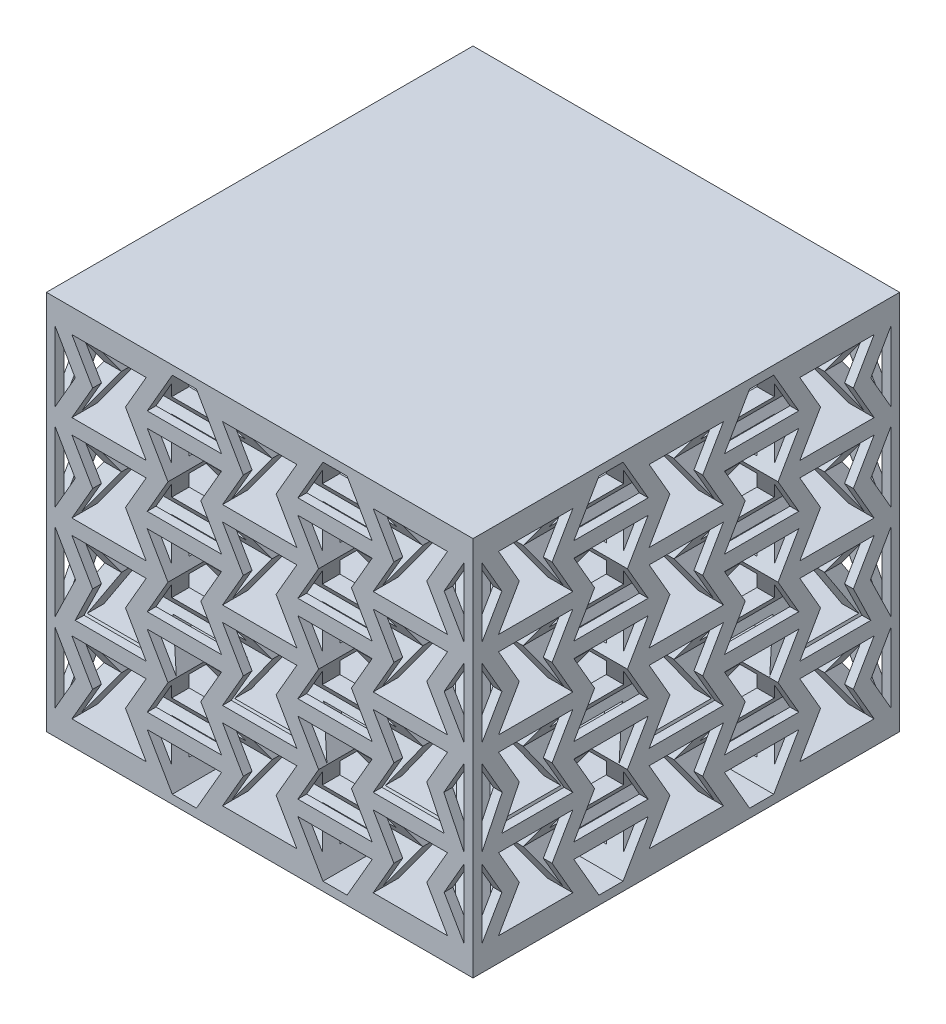
SolidWorks part; units mm, degrees
ref_plane "Front Plane" through (0, 0, 0) normal (0, 0, 1) x (1, 0, 0)
ref_plane "Top Plane" through (0, 0, 0) normal (0, 1, 0) x (1, 0, 0)
ref_plane "Right Plane" through (0, 0, 0) normal (1, 0, 0) x (0, 0, -1)
sketch "Sketch1" plane through (0, 0, 0) normal (0, 0, 1) x (1, 0, 0)
  line L0 (-9.5977, -9.2636) -> (10.4023, -9.2636) construction
  line L1 (10.4023, -9.2636) -> (5.4023, -0.6034) construction
  line L2 (5.4023, -0.6034) -> (10.4023, 8.0569) construction
  line L3 (10.4023, 8.0569) -> (-9.5977, 8.0569) construction
  line L4 (-9.5977, 8.0569) -> (-4.5977, -0.6034) construction
  line L5 (-4.5977, -0.6034) -> (-9.5977, -9.2636) construction
  line L6 (-9.5977, -26.5841) -> (10.4023, -26.5841) construction
  line L7 (10.4023, -26.5841) -> (5.4023, -17.9239) construction
  line L8 (5.4023, -17.9239) -> (10.4023, -9.2636) construction
  line L9 (-9.5977, -9.2636) -> (-4.5977, -17.9239) construction
  line L10 (-4.5977, -17.9239) -> (-9.5977, -26.5841) construction
  line L11 (-8.7413, -43.9047) -> (10.4023, -43.9047) construction
  line L12 (10.4023, -43.9047) -> (5.4023, -35.2444) construction
  line L13 (5.4023, -35.2444) -> (10.4023, -26.5841) construction
  line L14 (-9.5977, -26.5841) -> (-4.5628, -35.3049) construction
  line L15 (-4.5628, -35.3049) -> (-8.7413, -43.9047) construction
  line L16 (-9.5977, -61.2252) -> (10.4023, -61.2252) construction
  line L17 (10.4023, -61.2252) -> (5.4023, -52.5649) construction
  line L18 (5.4023, -52.5649) -> (10.4023, -43.9047) construction
  line L19 (-9.5977, -43.9047) -> (-4.5977, -52.5649) construction
  line L20 (-4.5977, -52.5649) -> (-9.5977, -61.2252) construction
  line L21 (5.4023, -0.6034) -> (25.4023, -0.6034) construction
  line L22 (5.4023, -17.9239) -> (25.4023, -17.9239) construction
  line L23 (20.4023, -9.2636) -> (40.4023, -9.2636) construction
  line L24 (40.4023, -9.2636) -> (35.4023, -0.6034) construction
  line L25 (5.4023, -35.2444) -> (25.4023, -35.2444) construction
  line L26 (5.4023, -52.5649) -> (25.4023, -52.5649) construction
  line L27 (35.4023, -0.6034) -> (40.4023, 8.0569) construction
  line L28 (40.4023, 8.0569) -> (20.4023, 8.0569) construction
  line L29 (20.4023, 8.0569) -> (25.4023, -0.6034) construction
  line L30 (25.4023, -0.6034) -> (20.4023, -9.2636) construction
  line L31 (20.4023, -26.5841) -> (40.4023, -26.5841) construction
  line L32 (40.4023, -26.5841) -> (35.4023, -17.9239) construction
  line L33 (35.4023, -17.9239) -> (40.4023, -9.2636) construction
  line L34 (20.4023, -9.2636) -> (25.4023, -17.9239) construction
  line L35 (25.4023, -17.9239) -> (20.4023, -26.5841) construction
  line L36 (20.4023, -43.9047) -> (40.4023, -43.9047) construction
  line L37 (40.4023, -43.9047) -> (35.4023, -35.2444) construction
  line L38 (35.4023, -35.2444) -> (40.4023, -26.5841) construction
  line L39 (20.4023, -26.5841) -> (25.4023, -35.2444) construction
  line L40 (25.4023, -35.2444) -> (20.4023, -43.9047) construction
  line L41 (20.4023, -61.2252) -> (40.4023, -61.2252) construction
  line L42 (40.4023, -61.2252) -> (35.4023, -52.5649) construction
  line L43 (35.4023, -52.5649) -> (40.4023, -43.9047) construction
  line L44 (20.4023, -43.9047) -> (25.4023, -52.5649) construction
  line L45 (25.4023, -52.5649) -> (20.4023, -61.2252) construction
  line L46 (35.4023, -0.6034) -> (55.4023, -0.6034) construction
  line L47 (35.4023, -17.9239) -> (55.4023, -17.9239) construction
  line L48 (35.4023, -35.2444) -> (55.4023, -35.2444) construction
  line L49 (35.4023, -52.5649) -> (55.4023, -52.5649) construction
  line L50 (50.4023, -9.2636) -> (70.4023, -9.2636) construction
  line L51 (70.4023, -9.2636) -> (65.4023, -0.6034) construction
  line L52 (65.4023, -0.6034) -> (70.4023, 8.0569) construction
  line L53 (70.4023, 8.0569) -> (50.4023, 8.0569) construction
  line L54 (50.4023, 8.0569) -> (55.4023, -0.6034) construction
  line L55 (55.4023, -0.6034) -> (50.4023, -9.2636) construction
  line L56 (50.4023, -26.5841) -> (70.4023, -26.5841) construction
  line L57 (70.4023, -26.5841) -> (65.4023, -17.9239) construction
  line L58 (65.4023, -17.9239) -> (70.4023, -9.2636) construction
  line L59 (50.4023, -9.2636) -> (55.4023, -17.9239) construction
  line L60 (55.4023, -17.9239) -> (50.4023, -26.5841) construction
  line L61 (50.4023, -43.9047) -> (69.5458, -43.9047) construction
  line L62 (69.5458, -43.9047) -> (65.3673, -35.3049) construction
  line L63 (65.3673, -35.3049) -> (70.4023, -26.5841) construction
  line L64 (50.4023, -26.5841) -> (55.4023, -35.2444) construction
  line L65 (55.4023, -35.2444) -> (50.4023, -43.9047) construction
  line L66 (50.4023, -61.2252) -> (70.4023, -61.2252) construction
  line L67 (70.4023, -61.2252) -> (65.4023, -52.5649) construction
  line L68 (65.4023, -52.5649) -> (70.4023, -43.9047) construction
  line L69 (50.4023, -43.9047) -> (55.4023, -52.5649) construction
  line L70 (55.4023, -52.5649) -> (50.4023, -61.2252) construction
  line L71 (-6.9997, -10.7636) -> (7.8042, -10.7636)
  line L72 (12.1343, -9.2636) -> (8.0003, -2.1034)
  line L73 (8.0003, 0.8966) -> (13.0003, 9.5569)
  line L75 (-10.3298, 6.3248) -> (-6.3298, -0.6034)
  line L76 (-6.3298, -0.6034) -> (-10.3298, -7.5316)
  line L77 (-10.3298, -10.9957) -> (-6.3298, -17.9239)
  line L78 (-6.3298, -17.9239) -> (-10.3298, -24.8521)
  line L80 (12.1343, -26.5841) -> (8.0003, -19.4239)
  line L81 (8.0003, -16.4239) -> (12.1343, -9.2636)
  line L82 (-10.3298, -28.3162) -> (-6.2599, -35.3655)
  line L83 (-6.2599, -35.3655) -> (-10.3298, -43.7416)
  line L85 (12.1343, -43.9047) -> (8.0003, -36.7444)
  line L86 (8.0003, -33.7444) -> (12.1343, -26.5841)
  line L87 (-10.3298, -45.6367) -> (-6.3298, -52.5649)
  line L88 (-6.3298, -52.5649) -> (-10.3298, -59.4931)
  line L90 (13.0003, -62.7252) -> (8.0003, -54.0649)
  line L91 (8.0003, -51.0649) -> (12.1343, -43.9047)
  line L92 (19.1032, -10.0136) -> (23.6702, -17.9239) construction
  line L93 (38.0003, -2.1034) -> (52.8042, -2.1034)
  line L94 (23.0003, -10.7636) -> (37.8042, -10.7636)
  line L95 (42.1343, -9.2636) -> (38.0003, -2.1034)
  line L96 (38.0003, 0.8966) -> (43.0003, 9.5569)
  line L98 (17.8042, 9.5569) -> (22.8042, 0.8966)
  line L99 (22.8042, -2.1034) -> (18.6702, -9.2636)
  line L100 (38.0003, -33.7444) -> (52.8042, -33.7444)
  line L101 (38.0003, -51.0649) -> (52.8042, -51.0649)
  line L102 (18.6702, -9.2636) -> (22.8042, -16.4239)
  line L103 (22.8042, -19.4239) -> (18.6702, -26.5841)
  line L105 (42.1343, -26.5841) -> (38.0003, -19.4239)
  line L106 (38.0003, -16.4239) -> (42.1343, -9.2636)
  line L107 (18.6702, -26.5841) -> (22.8042, -33.7444)
  line L108 (22.8042, -36.7444) -> (18.6702, -43.9047)
  line L110 (42.1343, -43.9047) -> (38.0003, -36.7444)
  line L111 (38.0003, -33.7444) -> (42.1343, -26.5841)
  line L112 (18.6702, -43.9047) -> (22.8042, -51.0649)
  line L113 (22.8042, -54.0649) -> (17.8042, -62.7252)
  line L115 (43.0003, -62.7252) -> (38.0003, -54.0649)
  line L116 (38.0003, -51.0649) -> (42.1343, -43.9047)
  line L117 (49.1032, -10.0136) -> (53.6702, -17.9239) construction
  line L118 (49.1032, -27.3341) -> (53.6702, -35.2444) construction
  line L119 (38.0003, -36.7444) -> (52.8042, -36.7444)
  line L120 (38.0003, -54.0649) -> (52.8042, -54.0649)
  line L122 (71.1343, -7.5316) -> (67.1343, -0.6034)
  line L123 (67.1343, -0.6034) -> (71.1343, 6.3248)
  line L125 (47.8042, 9.5569) -> (52.8042, 0.8966)
  line L126 (52.8042, -2.1034) -> (48.6702, -9.2636)
  line L127 (48.6702, -9.2636) -> (52.8042, -16.4239)
  line L128 (52.8042, -19.4239) -> (48.6702, -26.5841)
  line L129 (19.1032, -27.3341) -> (23.6702, -35.2444) construction
  line L130 (71.1343, -24.8521) -> (67.1343, -17.9239)
  line L131 (67.1343, -17.9239) -> (71.1343, -10.9957)
  line L132 (48.6702, -26.5841) -> (52.8042, -33.7444)
  line L133 (52.8042, -36.7444) -> (48.6702, -43.9047)
  line L135 (71.1343, -43.7416) -> (67.0644, -35.3655)
  line L136 (67.0644, -35.3655) -> (71.1343, -28.3162)
  line L137 (48.6702, -43.9047) -> (52.8042, -51.0649)
  line L138 (52.8042, -54.0649) -> (47.8042, -62.7252)
  line L140 (71.1343, -59.4931) -> (67.1343, -52.5649)
  line L141 (67.1343, -52.5649) -> (71.1343, -45.6367)
  line L142 (-6.9997, -7.7636) -> (7.8042, -7.7636)
  line L143 (7.8042, -7.7636) -> (3.6702, -0.6034)
  line L144 (3.6702, -0.6034) -> (7.8042, 6.5569)
  line L145 (7.8042, 6.5569) -> (-6.9997, 6.5569)
  line L146 (-6.9997, 6.5569) -> (-2.8657, -0.6034)
  line L147 (-2.8657, -0.6034) -> (-6.9997, -7.7636)
  line L148 (-6.9997, -10.7636) -> (-2.8657, -17.9239)
  line L149 (-2.8657, -17.9239) -> (-6.9997, -25.0841)
  line L150 (-6.9997, -25.0841) -> (7.8042, -25.0841)
  line L151 (7.8042, -25.0841) -> (3.6702, -17.9239)
  line L152 (3.6702, -17.9239) -> (7.8042, -10.7636)
  line L153 (-6.9997, -28.0841) -> (-2.8657, -35.2444)
  line L154 (-2.8657, -35.2444) -> (-6.3448, -42.4047)
  line L155 (-6.3448, -42.4047) -> (7.8042, -42.4047)
  line L156 (7.8042, -42.4047) -> (3.6702, -35.2444)
  line L157 (3.6702, -35.2444) -> (7.8042, -28.0841)
  line L158 (-6.9997, -45.4047) -> (-2.8657, -52.5649)
  line L159 (-2.8657, -52.5649) -> (-6.9997, -59.7252)
  line L160 (-6.9997, -59.7252) -> (7.8042, -59.7252)
  line L161 (7.8042, -59.7252) -> (3.6702, -52.5649)
  line L162 (3.6702, -52.5649) -> (7.8042, -45.4047)
  line L163 (8.0003, 0.8966) -> (22.8042, 0.8966)
  line L164 (8.0003, -16.4239) -> (22.8042, -16.4239)
  line L165 (23.0003, -7.7636) -> (37.8042, -7.7636)
  line L166 (37.8042, -7.7636) -> (33.6702, -0.6034)
  line L167 (33.6702, -0.6034) -> (37.8042, 6.5569)
  line L168 (37.8042, 6.5569) -> (23.0003, 6.5569)
  line L169 (23.0003, 6.5569) -> (27.1343, -0.6034)
  line L170 (27.1343, -0.6034) -> (23.0003, -7.7636)
  line L171 (8.0003, -33.7444) -> (22.8042, -33.7444)
  line L172 (8.0003, -51.0649) -> (22.8042, -51.0649)
  line L173 (23.0003, -10.7636) -> (27.1343, -17.9239)
  line L174 (27.1343, -17.9239) -> (23.0003, -25.0841)
  line L175 (23.0003, -25.0841) -> (37.8042, -25.0841)
  line L176 (37.8042, -25.0841) -> (33.6702, -17.9239)
  line L177 (33.6702, -17.9239) -> (37.8042, -10.7636)
  line L178 (23.0003, -28.0841) -> (27.1343, -35.2444)
  line L179 (27.1343, -35.2444) -> (23.0003, -42.4047)
  line L180 (23.0003, -42.4047) -> (37.8042, -42.4047)
  line L181 (37.8042, -42.4047) -> (33.6702, -35.2444)
  line L182 (33.6702, -35.2444) -> (37.8042, -28.0841)
  line L183 (23.0003, -45.4047) -> (27.1343, -52.5649)
  line L184 (27.1343, -52.5649) -> (23.0003, -59.7252)
  line L185 (23.0003, -59.7252) -> (37.8042, -59.7252)
  line L186 (37.8042, -59.7252) -> (33.6702, -52.5649)
  line L187 (33.6702, -52.5649) -> (37.8042, -45.4047)
  line L188 (38.0003, 0.8966) -> (52.8042, 0.8966)
  line L189 (38.0003, -19.4239) -> (52.8042, -19.4239)
  line L190 (-10.8968, -44.6547) -> (-6.3298, -52.5649) construction
  line L191 (-10.3298, 6.3248) -> (-10.3298, -7.5316)
  line L192 (53.0003, -7.7636) -> (67.8042, -7.7636)
  line L193 (67.8042, -7.7636) -> (63.6702, -0.6034)
  line L194 (63.6702, -0.6034) -> (67.8042, 6.5569)
  line L195 (67.8042, 6.5569) -> (53.0003, 6.5569)
  line L196 (53.0003, 6.5569) -> (57.1343, -0.6034)
  line L197 (57.1343, -0.6034) -> (53.0003, -7.7636)
  line L198 (53.0003, -10.7636) -> (57.1343, -17.9239)
  line L199 (57.1343, -17.9239) -> (53.0003, -25.0841)
  line L200 (53.0003, -25.0841) -> (67.8042, -25.0841)
  line L201 (67.8042, -25.0841) -> (63.6702, -17.9239)
  line L202 (63.6702, -17.9239) -> (67.8042, -10.7636)
  line L203 (53.0003, -28.0841) -> (57.1343, -35.2444)
  line L204 (57.1343, -35.2444) -> (53.0003, -42.4047)
  line L205 (53.0003, -42.4047) -> (67.1493, -42.4047)
  line L206 (67.1493, -42.4047) -> (63.6702, -35.2444)
  line L207 (63.6702, -35.2444) -> (67.8042, -28.0841)
  line L208 (53.0003, -45.4047) -> (57.1343, -52.5649)
  line L209 (57.1343, -52.5649) -> (53.0003, -59.7252)
  line L210 (53.0003, -59.7252) -> (67.8042, -59.7252)
  line L211 (67.8042, -59.7252) -> (63.6702, -52.5649)
  line L212 (63.6702, -52.5649) -> (67.8042, -45.4047)
  line L213 (-10.8968, -10.0136) -> (-6.3298, -17.9239) construction
  line L214 (-8.2987, -8.5136) -> (-2.8657, -17.9239) construction
  line L215 (7.1343, -17.9239) -> (11.7013, -10.0136) construction
  line L216 (-6.3298, -0.6034) -> (-12.1958, -10.7636) construction
  line L217 (-12.1958, -10.7636) -> (13.0003, -10.7636) construction
  line L218 (3.6702, -17.9239) -> (9.1032, -8.5136) construction
  line L219 (8.0003, -2.1034) -> (22.8042, -2.1034)
  line L220 (13.0003, -10.7636) -> (7.1343, -0.6034) construction
  line L221 (5.4023, 0.8966) -> (25.4023, 0.8966) construction
  line L222 (7.1343, -0.6034) -> (13.0003, 9.5569) construction
  line L223 (17.8042, 9.5569) -> (23.6702, -0.6034) construction
  line L224 (23.6702, -0.6034) -> (17.8042, -10.7636) construction
  line L225 (21.7013, -8.5136) -> (27.1343, -17.9239) construction
  line L226 (37.1343, -17.9239) -> (41.7013, -10.0136) construction
  line L227 (17.8042, -10.7636) -> (43.0003, -10.7636) construction
  line L228 (33.6702, -17.9239) -> (39.1032, -8.5136) construction
  line L229 (8.0003, -19.4239) -> (22.8042, -19.4239)
  line L230 (43.0003, -10.7636) -> (37.1343, -0.6034) construction
  line L231 (5.4023, -16.4239) -> (25.4023, -16.4239) construction
  line L232 (13.0003, -28.0841) -> (7.1343, -17.9239) construction
  line L233 (23.6702, -17.9239) -> (17.8042, -28.0841) construction
  line L234 (35.4023, 0.8966) -> (55.4023, 0.8966) construction
  line L235 (53.6702, -0.6034) -> (47.8042, -10.7636) construction
  line L236 (47.8042, 9.5569) -> (53.6702, -0.6034) construction
  line L237 (51.7013, -8.5136) -> (57.1343, -17.9239) construction
  line L238 (63.6702, -17.9239) -> (69.1032, -8.5136) construction
  line L239 (67.1343, -17.9239) -> (71.7013, -10.0136) construction
  line L240 (53.0003, -10.7636) -> (67.8042, -10.7636)
  line L241 (47.8042, -10.7636) -> (73.0003, -10.7636) construction
  line L242 (73.0003, -10.7636) -> (67.1343, -0.6034) construction
  line L243 (38.0003, -16.4239) -> (52.8042, -16.4239)
  line L244 (63.6702, -35.2444) -> (69.1032, -25.8341) construction
  line L245 (53.6702, -17.9239) -> (47.8042, -28.0841) construction
  line L246 (51.7013, -25.8341) -> (57.1343, -35.2444) construction
  line L247 (43.0003, -28.0841) -> (37.1343, -17.9239) construction
  line L248 (67.0644, -35.3655) -> (71.7013, -27.3341) construction
  line L249 (53.0003, -28.0841) -> (67.8042, -28.0841)
  line L250 (47.8042, -28.0841) -> (73.0003, -28.0841) construction
  line L251 (73.0003, -28.0841) -> (67.1343, -17.9239) construction
  line L252 (37.1343, -0.6034) -> (43.0003, 9.5569) construction
  line L253 (21.7013, -25.8341) -> (27.1343, -35.2444) construction
  line L254 (33.6702, -35.2444) -> (39.1032, -25.8341) construction
  line L255 (37.1343, -35.2444) -> (41.7013, -27.3341) construction
  line L256 (23.0003, -28.0841) -> (37.8042, -28.0841)
  line L257 (17.8042, -28.0841) -> (43.0003, -28.0841) construction
  line L258 (-10.8968, -27.3341) -> (-6.2599, -35.3655) construction
  line L259 (3.6702, -35.2444) -> (9.1032, -25.8341) construction
  line L260 (-8.2987, -25.8341) -> (-2.8657, -35.2444) construction
  line L261 (7.1343, -35.2444) -> (11.7013, -27.3341) construction
  line L262 (-6.9997, -28.0841) -> (7.8042, -28.0841)
  line L263 (-6.3298, -17.9239) -> (-12.1958, -28.0841) construction
  line L264 (-12.1958, -28.0841) -> (13.0003, -28.0841) construction
  line L265 (8.0003, -36.7444) -> (22.8042, -36.7444)
  line L266 (5.4023, -33.7444) -> (25.4023, -33.7444) construction
  line L267 (13.0003, -45.4047) -> (7.1343, -35.2444) construction
  line L268 (23.6702, -35.2444) -> (17.8042, -45.4047) construction
  line L269 (35.4023, -36.7444) -> (55.4023, -36.7444) construction
  line L270 (43.0003, -45.4047) -> (37.1343, -35.2444) construction
  line L271 (53.6702, -35.2444) -> (47.8042, -45.4047) construction
  line L272 (3.6702, -52.5649) -> (9.1032, -43.1547) construction
  line L273 (-8.2987, -43.1547) -> (-2.8657, -52.5649) construction
  line L274 (21.7013, -43.1547) -> (27.1343, -52.5649) construction
  line L275 (33.6702, -52.5649) -> (39.1032, -43.1547) construction
  line L276 (51.7013, -43.1547) -> (57.1343, -52.5649) construction
  line L277 (63.6702, -52.5649) -> (69.1032, -43.1547) construction
  line L278 (7.1343, -52.5649) -> (11.7013, -44.6547) construction
  line L279 (19.1032, -44.6547) -> (23.6702, -52.5649) construction
  line L280 (37.1343, -52.5649) -> (41.7013, -44.6547) construction
  line L281 (49.1032, -44.6547) -> (53.6702, -52.5649) construction
  line L282 (67.1343, -52.5649) -> (71.7013, -44.6547) construction
  line L283 (53.0003, -45.4047) -> (67.8042, -45.4047)
  line L284 (71.9423, -45.4047) -> (67.0644, -35.3655) construction
  line L285 (47.8042, -45.4047) -> (71.9423, -45.4047) construction
  line L286 (23.0003, -45.4047) -> (37.8042, -45.4047)
  line L287 (17.8042, -45.4047) -> (43.0003, -45.4047) construction
  line L288 (-6.9997, -45.4047) -> (7.8042, -45.4047)
  line L289 (-11.1378, -45.4047) -> (13.0003, -45.4047) construction
  line L290 (8.0003, -54.0649) -> (22.8042, -54.0649)
  line L291 (-6.2599, -35.3655) -> (-11.1378, -45.4047) construction
  line L292 (5.4023, -51.0649) -> (25.4023, -51.0649) construction
  line L293 (13.0003, -62.7252) -> (7.1343, -52.5649) construction
  line L294 (23.6702, -52.5649) -> (17.8042, -62.7252) construction
  line L295 (71.1343, 6.3248) -> (71.1343, -7.5316)
  line L296 (35.4023, -54.0649) -> (55.4023, -54.0649) construction
  line L297 (53.6702, -52.5649) -> (47.8042, -62.7252) construction
  line L298 (43.0003, -62.7252) -> (37.1343, -52.5649) construction
  line L299 (13.0003, -62.7252) -> (17.8042, -62.7252)
  line L300 (13.0003, 9.5569) -> (-12.1958, 9.5569) construction
  line L301 (43.0003, 9.5569) -> (17.8042, 9.5569) construction
  line L302 (73.0003, 9.5569) -> (47.8042, 9.5569) construction
  line L303 (-12.1958, -62.7252) -> (13.0003, -62.7252) construction
  line L304 (17.8042, -62.7252) -> (43.0003, -62.7252) construction
  line L305 (47.8042, -62.7252) -> (73.0003, -62.7252) construction
  line L306 (13.0003, 9.5569) -> (17.8042, 9.5569)
  line L307 (-12.0798, 11.3069) -> (72.8843, 11.3069)
  line L308 (67.1343, -0.6034) -> (73.0003, 9.5569) construction
  line L309 (73.0003, -62.7252) -> (67.1343, -52.5649) construction
  line L310 (-6.3298, -52.5649) -> (-12.1958, -62.7252) construction
  line L311 (-12.1958, 9.5569) -> (-6.3298, -0.6034) construction
  line L312 (72.8843, 11.3069) -> (72.8843, -64.4752)
  line L313 (-12.0798, -64.4752) -> (72.8843, -64.4752)
  line L314 (-12.0798, 11.3069) -> (-12.0798, -64.4752)
  line L315 (-10.3298, -10.9957) -> (-10.3298, -24.8521)
  line L316 (-10.3298, 9.5569) -> (-10.3298, -62.7252) construction
  line L317 (71.1343, 9.5569) -> (71.1343, -62.7252) construction
  line L318 (-10.3298, -28.3162) -> (-10.3298, -43.7416)
  line L319 (71.1343, -28.3162) -> (71.1343, -43.7416)
  line L320 (71.1343, -10.9957) -> (71.1343, -24.8521)
  line L321 (-10.3298, -45.6367) -> (-10.3298, -59.4931)
  line L322 (71.1343, -45.6367) -> (71.1343, -59.4931)
  line L323 (43.0003, -62.7252) -> (47.8042, -62.7252)
  line L324 (-10.3298, -62.7252) -> (71.1343, -62.7252) construction
  line L325 (43.0003, 9.5569) -> (47.8042, 9.5569)
  line L327 (-10.3298, 9.5569) -> (71.1343, 9.5569) construction
  point P112 (5.4023, -2.1034)
  point P113 (25.4023, -2.1034)
  point P114 (5.4023, -19.4239)
  point P115 (25.4023, -19.4239)
  point P122 (5.4023, -36.7444)
  point P123 (25.4023, -36.7444)
  point P124 (5.4023, -54.0649)
  point P125 (25.4023, -54.0649)
  point P144 (35.4023, -2.1034)
  point P145 (55.4023, -2.1034)
  point P146 (35.4023, -19.4239)
  point P147 (55.4023, -19.4239)
  point P234 (35.4023, -16.4239)
  point P235 (55.4023, -16.4239)
  point P236 (35.4023, -33.7444)
  point P237 (55.4023, -33.7444)
  point P238 (35.4023, -51.0649)
  point P239 (55.4023, -51.0649)
  point P335 (-11.3298, -26.5841)
  point P338 (72.1343, -26.5841)
  dimension "D1" = 1.5
  dimension "D2" = 1.5
  dimension "D3" = 1.75
extrude "Boss-Extrude1" add sketch "Sketch1" along normal mid plane 84.96
sketch "Sketch2" plane through (72.8843, 0, 0) normal (1, 0, 0) x (0, 0, -1)
  line L0 (-39.9979, -9.2636) -> (-19.9979, -9.2636) construction
  line L1 (-19.9979, -9.2636) -> (-24.9979, -0.6034) construction
  line L2 (-24.9979, -0.6034) -> (-19.9979, 8.0569) construction
  line L3 (-19.9979, 8.0569) -> (-39.9979, 8.0569) construction
  line L4 (-39.9979, 8.0569) -> (-34.9979, -0.6034) construction
  line L5 (-34.9979, -0.6034) -> (-39.9979, -9.2636) construction
  line L6 (-39.9979, -26.5841) -> (-19.9979, -26.5841) construction
  line L7 (-19.9979, -26.5841) -> (-24.9979, -17.9239) construction
  line L8 (-24.9979, -17.9239) -> (-19.9979, -9.2636) construction
  line L9 (-39.9979, -9.2636) -> (-34.9979, -17.9239) construction
  line L10 (-34.9979, -17.9239) -> (-39.9979, -26.5841) construction
  line L11 (-39.1415, -43.9047) -> (-19.9979, -43.9047) construction
  line L12 (-19.9979, -43.9047) -> (-24.9979, -35.2444) construction
  line L13 (-24.9979, -35.2444) -> (-19.9979, -26.5841) construction
  line L14 (-39.9979, -26.5841) -> (-34.963, -35.3049) construction
  line L15 (-34.963, -35.3049) -> (-39.1415, -43.9047) construction
  line L16 (-39.9979, -61.2252) -> (-19.9979, -61.2252) construction
  line L17 (-19.9979, -61.2252) -> (-24.9979, -52.5649) construction
  line L18 (-24.9979, -52.5649) -> (-19.9979, -43.9047) construction
  line L19 (-39.9979, -43.9047) -> (-34.9979, -52.5649) construction
  line L20 (-34.9979, -52.5649) -> (-39.9979, -61.2252) construction
  line L21 (-24.9979, -0.6034) -> (-4.9979, -0.6034) construction
  line L22 (-24.9979, -17.9239) -> (-4.9979, -17.9239) construction
  line L23 (-9.9979, -9.2636) -> (10.0021, -9.2636) construction
  line L24 (10.0021, -9.2636) -> (5.0021, -0.6034) construction
  line L25 (-24.9979, -35.2444) -> (-4.9979, -35.2444) construction
  line L26 (-24.9979, -52.5649) -> (-4.9979, -52.5649) construction
  line L27 (5.0021, -0.6034) -> (10.0021, 8.0569) construction
  line L28 (10.0021, 8.0569) -> (-9.9979, 8.0569) construction
  line L29 (-9.9979, 8.0569) -> (-4.9979, -0.6034) construction
  line L30 (-4.9979, -0.6034) -> (-9.9979, -9.2636) construction
  line L31 (-9.9979, -26.5841) -> (10.0021, -26.5841) construction
  line L32 (10.0021, -26.5841) -> (5.0021, -17.9239) construction
  line L33 (5.0021, -17.9239) -> (10.0021, -9.2636) construction
  line L34 (-9.9979, -9.2636) -> (-4.9979, -17.9239) construction
  line L35 (-4.9979, -17.9239) -> (-9.9979, -26.5841) construction
  line L36 (-9.9979, -43.9047) -> (10.0021, -43.9047) construction
  line L37 (10.0021, -43.9047) -> (5.0021, -35.2444) construction
  line L38 (5.0021, -35.2444) -> (10.0021, -26.5841) construction
  line L39 (-9.9979, -26.5841) -> (-4.9979, -35.2444) construction
  line L40 (-4.9979, -35.2444) -> (-9.9979, -43.9047) construction
  line L41 (-9.9979, -61.2252) -> (10.0021, -61.2252) construction
  line L42 (10.0021, -61.2252) -> (5.0021, -52.5649) construction
  line L43 (5.0021, -52.5649) -> (10.0021, -43.9047) construction
  line L44 (-9.9979, -43.9047) -> (-4.9979, -52.5649) construction
  line L45 (-4.9979, -52.5649) -> (-9.9979, -61.2252) construction
  line L46 (5.0021, -0.6034) -> (25.0021, -0.6034) construction
  line L47 (5.0021, -17.9239) -> (25.0021, -17.9239) construction
  line L48 (5.0021, -35.2444) -> (25.0021, -35.2444) construction
  line L49 (5.0021, -52.5649) -> (25.0021, -52.5649) construction
  line L50 (20.0021, -9.2636) -> (40.0021, -9.2636) construction
  line L51 (40.0021, -9.2636) -> (35.0021, -0.6034) construction
  line L52 (35.0021, -0.6034) -> (40.0021, 8.0569) construction
  line L53 (40.0021, 8.0569) -> (20.0021, 8.0569) construction
  line L54 (20.0021, 8.0569) -> (25.0021, -0.6034) construction
  line L55 (25.0021, -0.6034) -> (20.0021, -9.2636) construction
  line L56 (20.0021, -26.5841) -> (40.0021, -26.5841) construction
  line L57 (40.0021, -26.5841) -> (35.0021, -17.9239) construction
  line L58 (35.0021, -17.9239) -> (40.0021, -9.2636) construction
  line L59 (20.0021, -9.2636) -> (25.0021, -17.9239) construction
  line L60 (25.0021, -17.9239) -> (20.0021, -26.5841) construction
  line L61 (20.0021, -43.9047) -> (39.1456, -43.9047) construction
  line L62 (39.1456, -43.9047) -> (34.9671, -35.3049) construction
  line L63 (34.9671, -35.3049) -> (40.0021, -26.5841) construction
  line L64 (20.0021, -26.5841) -> (25.0021, -35.2444) construction
  line L65 (25.0021, -35.2444) -> (20.0021, -43.9047) construction
  line L66 (20.0021, -61.2252) -> (40.0021, -61.2252) construction
  line L67 (40.0021, -61.2252) -> (35.0021, -52.5649) construction
  line L68 (35.0021, -52.5649) -> (40.0021, -43.9047) construction
  line L69 (20.0021, -43.9047) -> (25.0021, -52.5649) construction
  line L70 (25.0021, -52.5649) -> (20.0021, -61.2252) construction
  line L71 (-37.3999, -10.7636) -> (-22.596, -10.7636)
  line L72 (-18.2659, -9.2636) -> (-22.3999, -2.1034)
  line L73 (-22.3999, 0.8966) -> (-17.3999, 9.5569)
  line L74 (-40.73, 6.3248) -> (-36.73, -0.6034)
  line L75 (-36.73, -0.6034) -> (-40.73, -7.5316)
  line L76 (-40.73, -10.9957) -> (-36.73, -17.9239)
  line L77 (-36.73, -17.9239) -> (-40.73, -24.8521)
  line L78 (-18.2659, -26.5841) -> (-22.3999, -19.4239)
  line L79 (-22.3999, -16.4239) -> (-18.2659, -9.2636)
  line L80 (-40.73, -28.3162) -> (-36.6601, -35.3655)
  line L81 (-36.6601, -35.3655) -> (-40.73, -43.7416)
  line L82 (-18.2659, -43.9047) -> (-22.3999, -36.7444)
  line L83 (-22.3999, -33.7444) -> (-18.2659, -26.5841)
  line L84 (-40.73, -45.6367) -> (-36.73, -52.5649)
  line L85 (-36.73, -52.5649) -> (-40.73, -59.4931)
  line L86 (-17.3999, -62.7252) -> (-22.3999, -54.0649)
  line L87 (-22.3999, -51.0649) -> (-18.2659, -43.9047)
  line L88 (7.6001, -2.1034) -> (22.404, -2.1034)
  line L89 (-7.3999, -10.7636) -> (7.404, -10.7636)
  line L90 (11.7341, -9.2636) -> (7.6001, -2.1034)
  line L91 (7.6001, 0.8966) -> (12.6001, 9.5569)
  line L92 (-12.596, 9.5569) -> (-7.596, 0.8966)
  line L93 (-7.596, -2.1034) -> (-11.73, -9.2636)
  line L94 (7.6001, -33.7444) -> (22.404, -33.7444)
  line L95 (7.6001, -51.0649) -> (22.404, -51.0649)
  line L96 (-11.73, -9.2636) -> (-7.596, -16.4239)
  line L97 (-7.596, -19.4239) -> (-11.73, -26.5841)
  line L98 (11.7341, -26.5841) -> (7.6001, -19.4239)
  line L99 (7.6001, -16.4239) -> (11.7341, -9.2636)
  line L100 (-11.73, -26.5841) -> (-7.596, -33.7444)
  line L101 (-7.596, -36.7444) -> (-11.73, -43.9047)
  line L102 (11.7341, -43.9047) -> (7.6001, -36.7444)
  line L103 (7.6001, -33.7444) -> (11.7341, -26.5841)
  line L104 (-11.73, -43.9047) -> (-7.596, -51.0649)
  line L105 (-7.596, -54.0649) -> (-12.596, -62.7252)
  line L106 (12.6001, -62.7252) -> (7.6001, -54.0649)
  line L107 (7.6001, -51.0649) -> (11.7341, -43.9047)
  line L108 (7.6001, -36.7444) -> (22.404, -36.7444)
  line L109 (7.6001, -54.0649) -> (22.404, -54.0649)
  line L110 (40.7341, -7.5316) -> (36.7341, -0.6034)
  line L111 (36.7341, -0.6034) -> (40.7341, 6.3248)
  line L112 (17.404, 9.5569) -> (22.404, 0.8966)
  line L113 (22.404, -2.1034) -> (18.27, -9.2636)
  line L114 (18.27, -9.2636) -> (22.404, -16.4239)
  line L115 (22.404, -19.4239) -> (18.27, -26.5841)
  line L116 (40.7341, -24.8521) -> (36.7341, -17.9239)
  line L117 (36.7341, -17.9239) -> (40.7341, -10.9957)
  line L118 (18.27, -26.5841) -> (22.404, -33.7444)
  line L119 (22.404, -36.7444) -> (18.27, -43.9047)
  line L120 (40.7341, -43.7416) -> (36.6642, -35.3655)
  line L121 (36.6642, -35.3655) -> (40.7341, -28.3162)
  line L122 (18.27, -43.9047) -> (22.404, -51.0649)
  line L123 (22.404, -54.0649) -> (17.404, -62.7252)
  line L124 (40.7341, -59.4931) -> (36.7341, -52.5649)
  line L125 (36.7341, -52.5649) -> (40.7341, -45.6367)
  line L126 (-37.3999, -7.7636) -> (-22.596, -7.7636)
  line L127 (-22.596, -7.7636) -> (-26.73, -0.6034)
  line L128 (-26.73, -0.6034) -> (-22.596, 6.5569)
  line L129 (-22.596, 6.5569) -> (-37.3999, 6.5569)
  line L130 (-37.3999, 6.5569) -> (-33.2659, -0.6034)
  line L131 (-33.2659, -0.6034) -> (-37.3999, -7.7636)
  line L132 (-37.3999, -10.7636) -> (-33.2659, -17.9239)
  line L133 (-33.2659, -17.9239) -> (-37.3999, -25.0841)
  line L134 (-37.3999, -25.0841) -> (-22.596, -25.0841)
  line L135 (-22.596, -25.0841) -> (-26.73, -17.9239)
  line L136 (-26.73, -17.9239) -> (-22.596, -10.7636)
  line L137 (-37.3999, -28.0841) -> (-33.2659, -35.2444)
  line L138 (-33.2659, -35.2444) -> (-36.745, -42.4047)
  line L139 (-36.745, -42.4047) -> (-22.596, -42.4047)
  line L140 (-22.596, -42.4047) -> (-26.73, -35.2444)
  line L141 (-26.73, -35.2444) -> (-22.596, -28.0841)
  line L142 (-37.3999, -45.4047) -> (-33.2659, -52.5649)
  line L143 (-33.2659, -52.5649) -> (-37.3999, -59.7252)
  line L144 (-37.3999, -59.7252) -> (-22.596, -59.7252)
  line L145 (-22.596, -59.7252) -> (-26.73, -52.5649)
  line L146 (-26.73, -52.5649) -> (-22.596, -45.4047)
  line L147 (-22.3999, 0.8966) -> (-7.596, 0.8966)
  line L148 (-22.3999, -16.4239) -> (-7.596, -16.4239)
  line L149 (-7.3999, -7.7636) -> (7.404, -7.7636)
  line L150 (7.404, -7.7636) -> (3.27, -0.6034)
  line L151 (3.27, -0.6034) -> (7.404, 6.5569)
  line L152 (7.404, 6.5569) -> (-7.3999, 6.5569)
  line L153 (-7.3999, 6.5569) -> (-3.2659, -0.6034)
  line L154 (-3.2659, -0.6034) -> (-7.3999, -7.7636)
  line L155 (-22.3999, -33.7444) -> (-7.596, -33.7444)
  line L156 (-22.3999, -51.0649) -> (-7.596, -51.0649)
  line L157 (-7.3999, -10.7636) -> (-3.2659, -17.9239)
  line L158 (-3.2659, -17.9239) -> (-7.3999, -25.0841)
  line L159 (-7.3999, -25.0841) -> (7.404, -25.0841)
  line L160 (7.404, -25.0841) -> (3.27, -17.9239)
  line L161 (3.27, -17.9239) -> (7.404, -10.7636)
  line L162 (-7.3999, -28.0841) -> (-3.2659, -35.2444)
  line L163 (-3.2659, -35.2444) -> (-7.3999, -42.4047)
  line L164 (-7.3999, -42.4047) -> (7.404, -42.4047)
  line L165 (7.404, -42.4047) -> (3.27, -35.2444)
  line L166 (3.27, -35.2444) -> (7.404, -28.0841)
  line L167 (-7.3999, -45.4047) -> (-3.2659, -52.5649)
  line L168 (-3.2659, -52.5649) -> (-7.3999, -59.7252)
  line L169 (-7.3999, -59.7252) -> (7.404, -59.7252)
  line L170 (7.404, -59.7252) -> (3.27, -52.5649)
  line L171 (3.27, -52.5649) -> (7.404, -45.4047)
  line L172 (7.6001, 0.8966) -> (22.404, 0.8966)
  line L173 (7.6001, -19.4239) -> (22.404, -19.4239)
  line L174 (-40.73, 6.3248) -> (-40.73, -7.5316)
  line L175 (22.6001, -7.7636) -> (37.404, -7.7636)
  line L176 (37.404, -7.7636) -> (33.27, -0.6034)
  line L177 (33.27, -0.6034) -> (37.404, 6.5569)
  line L178 (37.404, 6.5569) -> (22.6001, 6.5569)
  line L179 (22.6001, 6.5569) -> (26.7341, -0.6034)
  line L180 (26.7341, -0.6034) -> (22.6001, -7.7636)
  line L181 (22.6001, -10.7636) -> (26.7341, -17.9239)
  line L182 (26.7341, -17.9239) -> (22.6001, -25.0841)
  line L183 (22.6001, -25.0841) -> (37.404, -25.0841)
  line L184 (37.404, -25.0841) -> (33.27, -17.9239)
  line L185 (33.27, -17.9239) -> (37.404, -10.7636)
  line L186 (22.6001, -28.0841) -> (26.7341, -35.2444)
  line L187 (26.7341, -35.2444) -> (22.6001, -42.4047)
  line L188 (22.6001, -42.4047) -> (36.7491, -42.4047)
  line L189 (36.7491, -42.4047) -> (33.27, -35.2444)
  line L190 (33.27, -35.2444) -> (37.404, -28.0841)
  line L191 (22.6001, -45.4047) -> (26.7341, -52.5649)
  line L192 (26.7341, -52.5649) -> (22.6001, -59.7252)
  line L193 (22.6001, -59.7252) -> (37.404, -59.7252)
  line L194 (37.404, -59.7252) -> (33.27, -52.5649)
  line L195 (33.27, -52.5649) -> (37.404, -45.4047)
  line L196 (-22.3999, -2.1034) -> (-7.596, -2.1034)
  line L197 (-22.3999, -19.4239) -> (-7.596, -19.4239)
  line L198 (22.6001, -10.7636) -> (37.404, -10.7636)
  line L199 (7.6001, -16.4239) -> (22.404, -16.4239)
  line L200 (22.6001, -28.0841) -> (37.404, -28.0841)
  line L201 (-7.3999, -28.0841) -> (7.404, -28.0841)
  line L202 (-37.3999, -28.0841) -> (-22.596, -28.0841)
  line L203 (-22.3999, -36.7444) -> (-7.596, -36.7444)
  line L204 (22.6001, -45.4047) -> (37.404, -45.4047)
  line L205 (-7.3999, -45.4047) -> (7.404, -45.4047)
  line L206 (-37.3999, -45.4047) -> (-22.596, -45.4047)
  line L207 (-22.3999, -54.0649) -> (-7.596, -54.0649)
  line L208 (40.7341, 6.3248) -> (40.7341, -7.5316)
  line L209 (-17.3999, -62.7252) -> (-12.596, -62.7252)
  line L210 (-17.3999, 9.5569) -> (-12.596, 9.5569)
  line L211 (-42.48, 11.3069) -> (42.4841, 11.3069)
  line L212 (42.4841, 11.3069) -> (42.4841, -64.4752)
  line L213 (-42.48, -64.4752) -> (42.4841, -64.4752)
  line L214 (-42.48, 11.3069) -> (-42.48, -64.4752)
  line L215 (-40.73, -10.9957) -> (-40.73, -24.8521)
  line L216 (-40.73, -28.3162) -> (-40.73, -43.7416)
  line L217 (40.7341, -28.3162) -> (40.7341, -43.7416)
  line L218 (40.7341, -10.9957) -> (40.7341, -24.8521)
  line L219 (-40.73, -45.6367) -> (-40.73, -59.4931)
  line L220 (40.7341, -45.6367) -> (40.7341, -59.4931)
  line L221 (12.6001, -62.7252) -> (17.404, -62.7252)
  line L222 (12.6001, 9.5569) -> (17.404, 9.5569)
  point P225 (-41.73, -26.5841)
  point P226 (41.7341, -26.5841)
extrude "Cut-Extrude3" cut sketch "Sketch2" against normal through all flip side to cut
